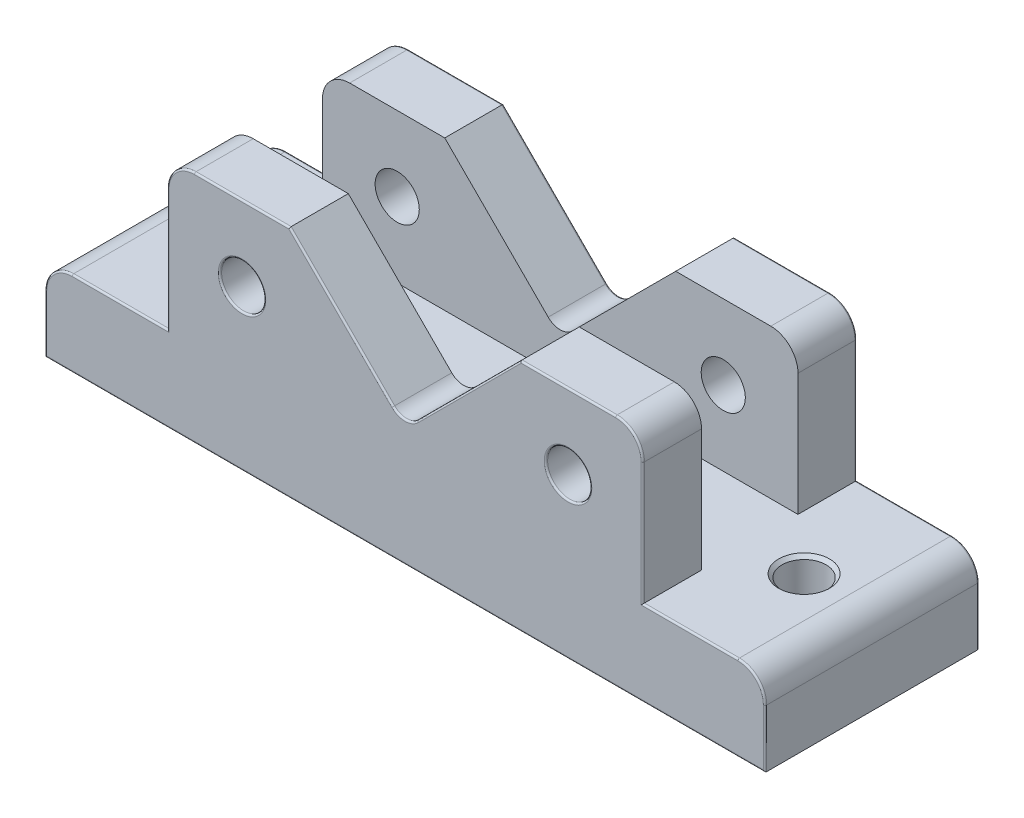
SolidWorks part; units mm, degrees
ref_plane "Front Plane" through (0, 0, 0) normal (0, 0, 1) x (1, 0, 0)
ref_plane "Top Plane" through (0, 0, 0) normal (0, 1, 0) x (1, 0, 0)
ref_plane "Right Plane" through (0, 0, 0) normal (1, 0, 0) x (0, 0, -1)
sketch "Sketch1" plane through (0, 0, 0) normal (0, 0, 1) x (1, 0, 0)
  line L0 (0, 64.7951) -> (0, 0) construction
  line L1 (0, 0) -> (106, 0) construction
  line L2 (0, 0) -> (0, 17)
  line L3 (8, 25) -> (36, 25)
  line L4 (36, 25) -> (36, 61)
  line L5 (44, 69) -> (72, 69)
  line L6 (72, 69) -> (102.4645, 38.5355)
  line L7 (106, 0) -> (106, 76.5639) construction
  line L8 (204, 25) -> (176, 25)
  line L9 (212, 0) -> (212, 17)
  line L10 (140, 69) -> (109.5355, 38.5355)
  line L11 (168, 69) -> (140, 69)
  line L12 (176, 25) -> (176, 61)
  line L13 (0, 0) -> (212, 0)
  arc A0 (36, 61) -> (44, 69) centre (44, 61) cw
  arc A1 (0, 17) -> (8, 25) centre (8, 17) cw
  arc A2 (212, 17) -> (204, 25) centre (204, 17) ccw
  arc A3 (176, 61) -> (168, 69) centre (168, 61) ccw
  arc A4 (102.4645, 38.5355) -> (109.5355, 38.5355) centre (106, 42.0711) ccw
  point P12 (36, 69)
  point P15 (0, 25)
  point P25 (212, 25)
  point P26 (176, 69)
  point P29 (106, 35)
  dimension "D7" = 8
  dimension "D8" = 5
  dimension "D1" = 25
  dimension "D2" = 36
  dimension "D3" = 44
  dimension "D4" = 36
  dimension "D5" = 34
  dimension "D6" = 45
extrude "Boss-Extrude1" add sketch "Sketch1" along normal mid plane 63
sketch "Sketch2" plane through (176, 0, 0) normal (1, 0, 0) x (0, 0, -1)
  line L26 (-31.5, 25) -> (31.5, 25) construction
  line L27 (-14.2, 25) -> (14.2, 25)
  line L28 (-14.2, 25) -> (-14.2, 69)
  line L29 (-14.2, 69) -> (14.2, 69)
  line L30 (14.2, 25) -> (14.2, 69)
  line L31 (0, 69) -> (0, 25) construction
  line L32 (-14.2, 47) -> (14.2, 47) construction
  line L33 (-31.5, 69) -> (31.5, 69) construction
  line L34 (0, 47) -> (0, 0) construction
  point P210 (0, 47)
  dimension "D1" = 28.4
extrude "Cut-Extrude1" cut sketch "Sketch2" against normal up to surface (140 mm away) up to face at (36, 43, 0)
sketch "Sketch3" plane through (0, 0, 31.5) normal (0, 0, 1) x (1, 0, 0)
  line L0 (106, 0) -> (106, 77.8298) construction
  line L1 (0, 0) -> (212, 0) construction
  line L2 (72, 69) -> (44, 69) construction
  circle A0 centre (58, 47) radius 6.5
  circle A2 centre (154, 47) radius 6.5
  point P8 (48.013, 61.3538)
  point P9 (6.9299, 91.3102)
  dimension "D1" = 13
  dimension "D2" = 48
  dimension "D3" = 22
extrude "Cut-Extrude2" cut sketch "Sketch3" against normal through all
sketch "Sketch4" plane through (0, 25, 0) normal (0, 1, 0) x (1, 0, 0)
  line L0 (0, 0) -> (212, 0) construction
  line L1 (212, -31.5) -> (212, 31.5) construction
  line L2 (0, -31.5) -> (0, 31.5) construction
  circle A0 centre (20, 0) radius 6.5
  circle A1 centre (192, 0) radius 6.5
  dimension "D2" = 13
  dimension "D3" = 13
  dimension "D1" = 20
  dimension "D4" = 20
extrude "Cut-Extrude3" cut sketch "Sketch4" against normal through all
fillet "Fillet1" radius 0.5 36 edges at (212, 8.5, -31.5) (209.6569, 22.6569, -31.5) (190, 25, -31.5) (176, 43, -31.5) (173.6569, 66.6569, -31.5) (154, 69, -31.5) (124.7678, 53.7678, -31.5) (106, 37.0711, -31.5) (87.2322, 53.7678, -31.5) (58, 69, -31.5) (38.3431, 66.6569, -31.5) (36, 43, -31.5) (22, 25, -31.5) (2.3431, 22.6569, -31.5) (0, 8.5, -31.5) (106, 0, -31.5) (147.5, 47, -31.5) (64.5, 47, -31.5) (0, 8.5, 31.5) (2.3431, 22.6569, 31.5) (22, 25, 31.5) (36, 43, 31.5) (38.3431, 66.6569, 31.5) (58, 69, 31.5) (87.2322, 53.7678, 31.5) (106, 37.0711, 31.5) (124.7678, 53.7678, 31.5) (154, 69, 31.5) (173.6569, 66.6569, 31.5) (176, 43, 31.5) (190, 25, 31.5) (209.6569, 22.6569, 31.5) (212, 8.5, 31.5) (106, 0, 31.5) (147.5, 47, 31.5) (64.5, 47, 31.5)
chamfer "Chamfer1" distance 1 angle 45 2 edges at (192, 25, 6.5) (20, 25, 6.5)
